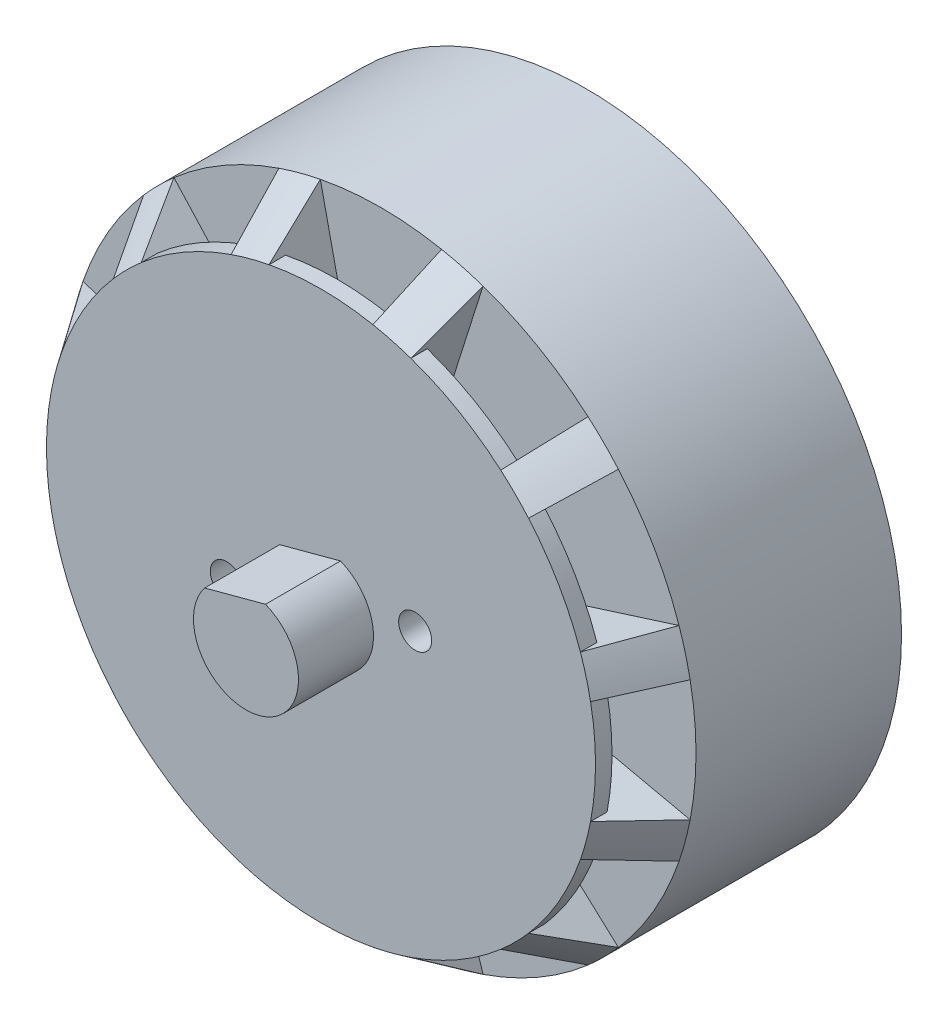
SolidWorks part; units mm, degrees
ref_plane "前视基准面" through (0, 0, 0) normal (0, 0, 1) x (1, 0, 0)
ref_plane "上视基准面" through (0, 0, 0) normal (0, 1, 0) x (1, 0, 0)
ref_plane "右视基准面" through (0, 0, 0) normal (1, 0, 0) x (0, 0, -1)
sketch "草图1" plane through (0, 0, 0) normal (0, 0, 1) x (1, 0, 0)
  circle A0 centre (0, 0) radius 21
  dimension "D1" = 42
extrude "凸台-拉伸1" add sketch "草图1" along normal blind 13.7
ref_plane "基准面1" through (0, 0, 17.7) normal (0, 0, 1) x (1, 0, 0)
sketch "草图2" plane through (0, 0, 17.7) normal (0, 0, 1) x (1, 0, 0)
  circle A0 centre (0, 0) radius 18.3
  dimension "D1" = 36.6
sketch "草图3" plane through (0, 0, 13.7) normal (0, 0, 1) x (1, 0, 0)
  circle A0 centre (0, 0) radius 21
  dimension "D1" = 42
loft "放样1" add profiles "草图3", "草图2"
sketch "草图4" plane through (0, 0, 17.7) normal (0, 0, 1) x (1, 0, 0)
  line L0 (0, 0) -> (21, 0) construction
  line L1 (0, 0) -> (20.2844, 5.4352)
  line L2 (0, 0) -> (20.2844, -5.4352)
  line L3 (20.6075, 4.0413) -> (6.9242, 1.0271)
  line L4 (20.6075, -4.0413) -> (6.9242, -1.0271)
  circle A0 centre (0, 0) radius 21 construction
  circle A1 centre (0, 0) radius 7
  circle A2 centre (0, 0) radius 21
  dimension "D2" = 14
  dimension "D1" = 15
  dimension "D3" = 1.4308
  dimension "D4" = 0.8
extrude "切除-拉伸1" cut sketch "草图4" against normal blind 4
pattern_circular "阵列(圆周)1" count 12 over 360 of "切除-拉伸1"
sketch "草图5" plane through (0, 0, 17.7) normal (0, 0, 1) x (1, 0, 0)
  circle A0 centre (0, 0) radius 18.3
  dimension "D1" = 36.6
extrude "凸台-拉伸2" add sketch "草图5" against normal blind 1.1
sketch "草图6" plane through (0, 0, 17.7) normal (0, 0, 1) x (1, 0, 0)
  line L0 (-2.7531, 2.1611) -> (1.3038, 3.2481)
  line L1 (20.2844, 5.4352) -> (-20.2844, -5.4352) construction
  arc A0 (-2.7531, 2.1611) -> (1.3038, 3.2481) centre (0, 0) ccw
  arc A1 (20.6075, 4.0413) -> (19.8672, 6.8039) centre (0, 0) ccw construction
  arc A2 (-20.6075, -4.0413) -> (-19.8672, -6.8039) centre (0, 0) ccw construction
  dimension "D1" = 7
  dimension "D2" = 2.8
extrude "凸台-拉伸3" add sketch "草图6" along normal blind 5
sketch "草图8" plane through (0, 0, 17.7) normal (0, 0, 1) x (1, 0, 0)
  line L0 (20.2844, 5.4352) -> (-20.2844, -5.4352) construction
  line L1 (-5.4352, 20.2844) -> (0, 0) construction
  arc A0 (20.6075, 4.0413) -> (19.8672, 6.8039) centre (0, 0) ccw construction
  arc A1 (-20.6075, -4.0413) -> (-19.8672, -6.8039) centre (0, 0) ccw construction
  arc A2 (-4.0413, 20.6075) -> (-6.8039, 19.8672) centre (0, 0) ccw construction
  circle A3 centre (6.2785, 1.6823) radius 3
  circle A4 centre (-6.2785, -1.6823) radius 3
  dimension "D1" = 6
  dimension "D2" = 13
extrude "凸台-拉伸4" add sketch "草图8" against normal blind 4
sketch "草图9" plane through (0, 0, 17.7) normal (0, 0, 1) x (1, 0, 0)
  circle A0 centre (6.2785, 1.6823) radius 1.1
  circle A1 centre (-6.2785, -1.6823) radius 1.1
  dimension "D1" = 2.2
  dimension "D2" = 2.2
extrude "切除-拉伸3" cut sketch "草图9" against normal blind 4
cosmetic thread "装饰螺纹线1" parameters "D2"=3
cosmetic thread "装饰螺纹线2" parameters "D2"=3
